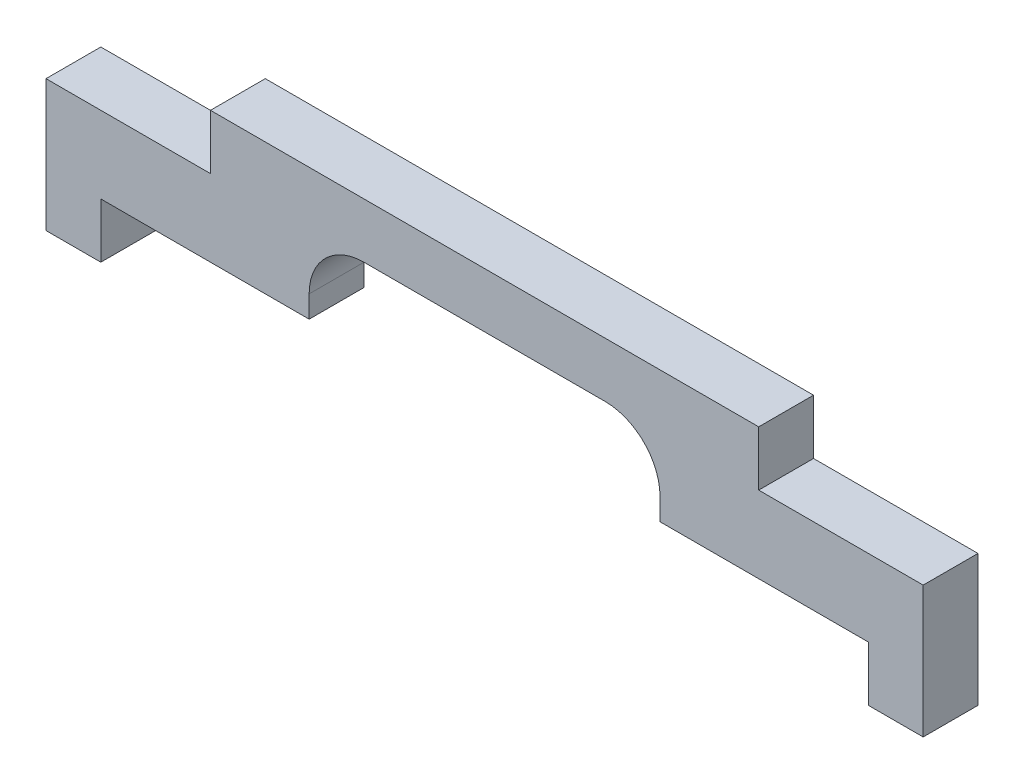
SolidWorks part; units mm, degrees
material "Balsa"
ref_plane "Plan de face" through (0, 0, 0) normal (0, 0, 1) x (1, 0, 0)
ref_plane "Plan de dessus" through (0, 0, 0) normal (0, 1, 0) x (1, 0, 0)
ref_plane "Plan de droite" through (0, 0, 0) normal (1, 0, 0) x (0, 0, -1)
sketch "Esquisse1" plane through (0, 0, 0) normal (0, 0, 1) x (1, 0, 0)
  line L0 (0, 0) -> (0, -35.9732) construction
  line L1 (-16, -12) -> (-16, -5)
  line L2 (-25, 0) -> (25, 0)
  line L3 (25, 0) -> (25, -5)
  line L4 (25, -5) -> (40, -5)
  line L5 (40, -5) -> (40, -17)
  line L6 (40, -17) -> (35, -17)
  line L7 (35, -17) -> (35, -12)
  line L8 (35, -12) -> (16, -12)
  line L9 (16, -12) -> (16, -5)
  line L10 (16, -5) -> (-16, -5)
  line L11 (-35, -12) -> (-16, -12)
  line L12 (-35, -17) -> (-35, -12)
  line L13 (-40, -17) -> (-35, -17)
  line L14 (-40, -5) -> (-40, -17)
  line L15 (-25, -5) -> (-40, -5)
  line L16 (-25, 0) -> (-25, -5)
  dimension "D1" = 50
  dimension "D2" = 5
  dimension "D3" = 5
  dimension "D4" = 5
  dimension "D5" = 32
  dimension "D6" = 80
  dimension "D7" = 7
extrude "Boss.-Extru.1" add sketch "Esquisse1" along normal blind 5
sketch "Esquisse2" plane through (0, 0, 5) normal (0, 0, 1) x (1, 0, 0)
  line L0 (-16, -10) -> (-16, -3.9004)
  line L1 (-16, -12) -> (-16, -5) construction
  line L2 (-16, -3.9004) -> (16, -3.9004)
  line L3 (0, 0) -> (0, -9.1107) construction
  line L4 (-16, -5) -> (16, -5) construction
  line L5 (-11, -5) -> (11, -5)
  line L6 (16, -10) -> (16, -3.9004)
  arc A0 (-16, -10) -> (-11, -5) centre (-11, -10) cw
  arc A1 (16, -10) -> (11, -5) centre (11, -10) ccw
  dimension "D1" = 5
extrude "Boss.-Extru.2" add sketch "Esquisse2" against normal blind 5
